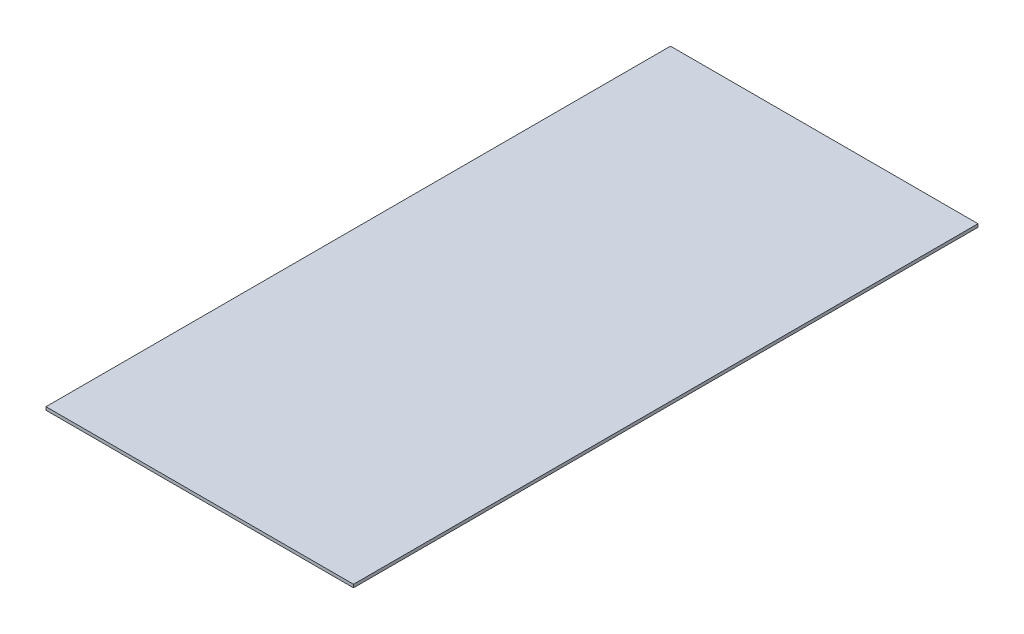
SolidWorks part; units mm, degrees
ref_plane "Alzado" through (0, 0, 0) normal (0, 0, 1) x (1, 0, 0)
ref_plane "Planta" through (0, 0, 0) normal (0, 1, 0) x (1, 0, 0)
ref_plane "Vista lateral" through (0, 0, 0) normal (1, 0, 0) x (0, 0, -1)
sketch "Croquis1" plane through (0, 0, 0) normal (0, 1, 0) x (1, 0, 0)
  line L1 (490, -995) -> (-490, -995)
  line L2 (490, -995) -> (490, 995)
  line L3 (490, 995) -> (-490, 995)
  line L4 (-490, -995) -> (-490, 995)
  line L5 (490, -995) -> (-490, 995) construction
  line L6 (490, 995) -> (-490, -995) construction
  point P0 (0, 0)
  dimension "D1" = 980
  dimension "D2" = 1990
extrude "Extruir1" add sketch "Croquis1" along normal blind 10
